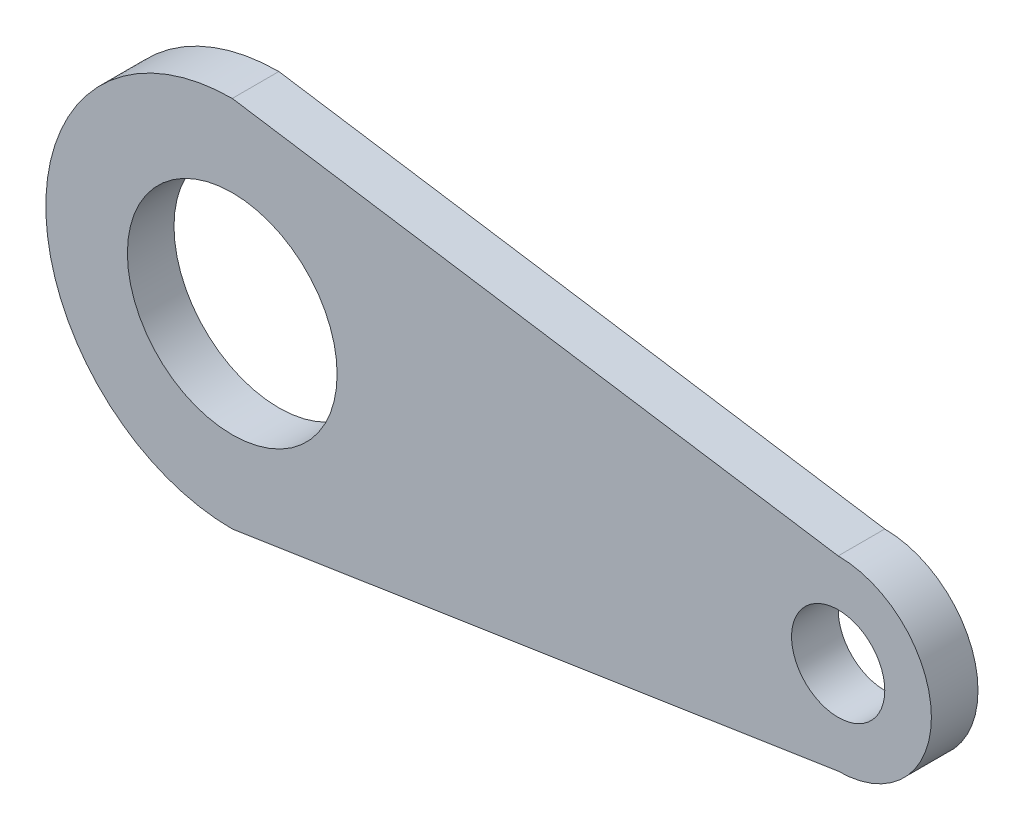
SolidWorks part; units mm, degrees
ref_plane "Front Plane" through (0, 0, 0) normal (0, 0, 1) x (1, 0, 0)
ref_plane "Top Plane" through (0, 0, 0) normal (0, 1, 0) x (1, 0, 0)
ref_plane "Right Plane" through (0, 0, 0) normal (1, 0, 0) x (0, 0, -1)
sketch "Sketch3" plane through (0, 0, 0) normal (0, 0, 1) x (1, 0, 0)
  line L0 (-107.7488, 0) -> (22.2512, 0) construction
  line L1 (-107.7488, 40) -> (22.2512, 20)
  line L2 (-107.7488, -40) -> (22.2512, -20)
  line L3 (-107.7488, 65.8895) -> (-107.7488, -64.7268) construction
  line L4 (22.2512, 47.673) -> (22.2512, -56.1999) construction
  circle A0 centre (-107.7488, 0) radius 22.5
  arc A1 (-107.7488, 40) -> (-107.7488, -40) centre (-107.7488, 0) ccw
  circle A2 centre (22.2512, 0) radius 10
  arc A3 (22.2512, -20) -> (22.2512, 20) centre (22.2512, 0) ccw
  dimension "D1" = 45
  dimension "D2" = 80
  dimension "D3" = 20
  dimension "D4" = 40
  dimension "D5" = 130
extrude "Boss-Extrude1" add sketch "Sketch3" along normal blind 10
